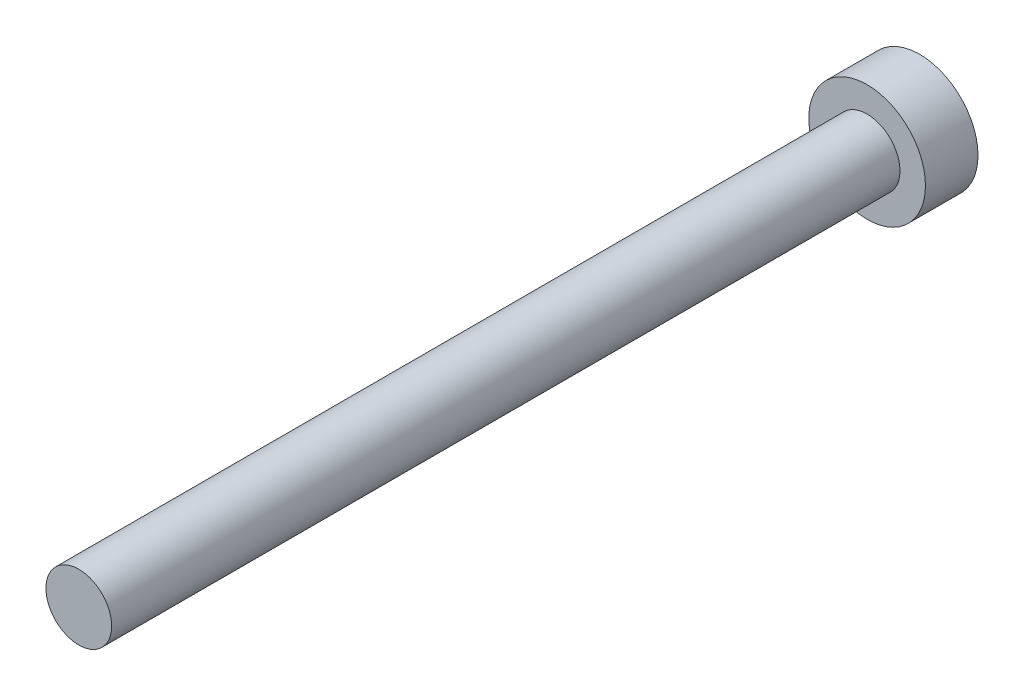
SolidWorks part; units mm, degrees
material "ABS"
ref_plane "Front Plane" through (0, 0, 0) normal (0, 0, 1) x (1, 0, 0)
ref_plane "Top Plane" through (0, 0, 0) normal (0, 1, 0) x (1, 0, 0)
ref_plane "Right Plane" through (0, 0, 0) normal (1, 0, 0) x (0, 0, -1)
sketch "Sketch2" plane through (0, 0, 0) normal (0, 0, 1) x (1, 0, 0)
  circle A0 centre (0, 0) radius 1.25
extrude "Boss-Extrude1" add sketch "Sketch2" along normal blind 30
sketch "Sketch3" plane through (0, 0, 0) normal (0, 0, 1) x (1, 0, 0)
  circle A0 centre (0, 0) radius 2.22
extrude "Boss-Extrude2" add sketch "Sketch3" against normal blind 2
